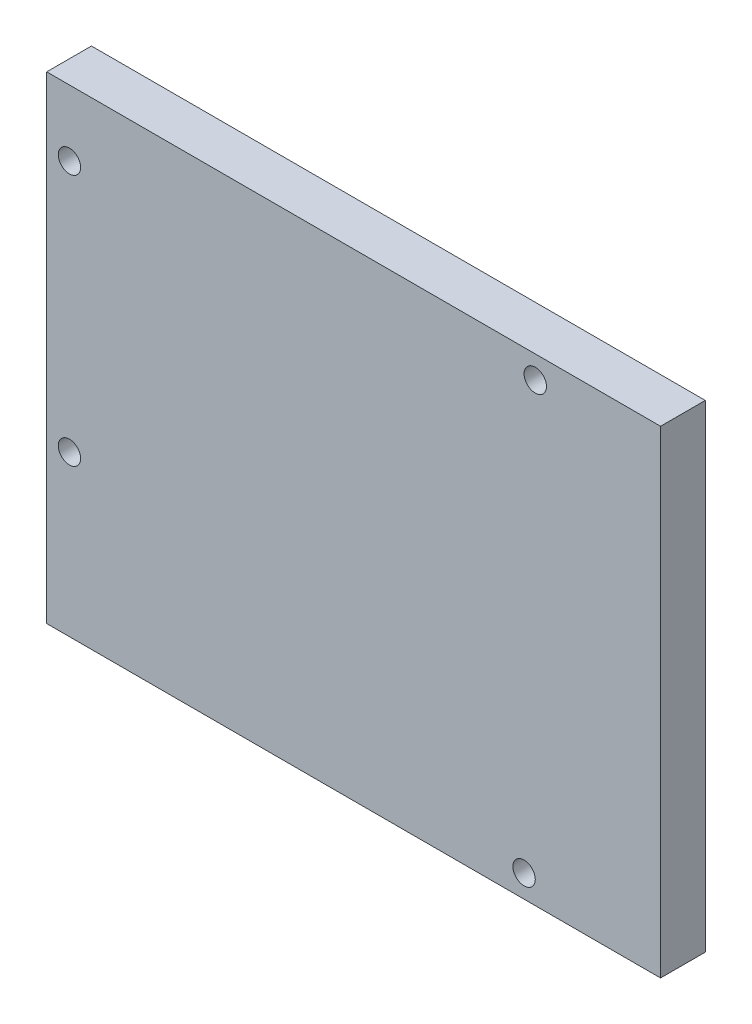
SolidWorks part; units mm, degrees
ref_plane "Front" through (0, 0, 0) normal (0, 0, 1) x (1, 0, 0)
ref_plane "Top" through (0, 0, 0) normal (0, 1, 0) x (1, 0, 0)
ref_plane "Right" through (0, 0, 0) normal (1, 0, 0) x (0, 0, -1)
sketch "arduinoOutline" plane through (0, 0, 0) normal (0, 0, 1) x (1, 0, 0)
  line L0 (0, 32.73) -> (2.54, 35.27) construction
  line L2 (0, 0) -> (0, 32.73) construction
  line L5 (2.54, 35.27) -> (2.54, 36.81) construction
  line L6 (3.54, 37.81) -> (67.6, 37.81) construction
  line L7 (68.6, 36.81) -> (68.6, -14.59) construction
  line L8 (67.6, -15.59) -> (4.06, -15.59) construction
  line L9 (4.06, -15.59) -> (2.54, -14.07) construction
  line L10 (2.54, -14.07) -> (2.54, -2.54) construction
  line L11 (2.54, -2.54) -> (0, 0) construction
  arc A0 (2.54, 36.81) -> (3.54, 37.81) centre (3.54, 36.81) cw construction
  arc A1 (68.6, -14.59) -> (67.6, -15.59) centre (67.6, -14.59) cw construction
  arc A2 (67.6, 37.81) -> (68.6, 36.81) centre (67.6, 36.81) cw construction
  point P8 (2.54, 37.81)
  point P13 (68.6, -15.59)
  point P16 (68.6, 37.81)
  point P17 (0, 0)
  dimension "D6" = 1
  dimension "D9" = 1
  dimension "D10" = 1
  dimension "D1" = 32.73
  dimension "D2" = 135
  dimension "D3" = 3.5921
  dimension "D4" = 2.54
  dimension "D5" = 66.06
  dimension "D7" = 53.4
  dimension "D8" = 64.54
  dimension "D11" = 135
  dimension "D12" = 2.1496
  dimension "D13" = 11.53
  dimension "D14" = 135
  dimension "D15" = 3.5921
sketch "mountingHolesSketch" plane through (0, 0, 0) normal (0, 0, 1) x (1, 0, 0)
  line L0 (0, 0) -> (0, 32.73) construction
  line L1 (67.6, -15.59) -> (4.06, -15.59) construction
  line L2 (3.54, 37.81) -> (67.6, 37.81) construction
  line L3 (68.6, 36.81) -> (68.6, -14.59) construction
  circle A0 centre (2.54, 2.28) radius 1.25
  circle A1 centre (2.54, 30.45) radius 1.25
  circle A2 centre (54.6, 35.27) radius 1.25
  circle A3 centre (53.35, -13.05) radius 1.25
  dimension "D9" = 2.5
  dimension "D1" = 2.54
  dimension "D2" = 17.87
  dimension "D3" = 2.54
  dimension "D4" = 7.36
  dimension "D5" = 2.54
  dimension "D6" = 14
  dimension "D7" = 2.54
  dimension "D8" = 15.25
sketch "Sketch4" plane through (0, 0, 0) normal (0, 0, 1) x (1, 0, 0)
  line L0 (0, 0) -> (0, 32.73) construction
  line L1 (0, 37.81) -> (68.6, 37.81)
  line L2 (0, 37.81) -> (0, -15.59)
  line L3 (0, -15.59) -> (68.6, -15.59)
  line L4 (68.6, 37.81) -> (68.6, -15.59)
  line L5 (68.6, 36.81) -> (68.6, -14.59) construction
  line L6 (3.54, 37.81) -> (67.6, 37.81) construction
  line L7 (67.6, -15.59) -> (4.06, -15.59) construction
extrude "bracketBase" add sketch "Sketch4" along normal blind 5
extrude "mountingHoles" cut sketch "mountingHolesSketch" against normal through all and the other way through all
